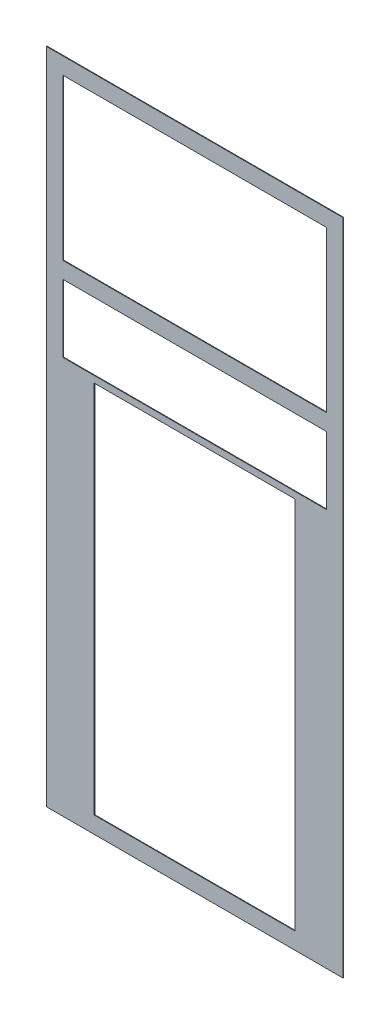
SolidWorks part; units mm, degrees
ref_plane "Alzado" through (0, 0, 0) normal (0, 0, 1) x (1, 0, 0)
ref_plane "Planta" through (0, 0, 0) normal (0, 1, 0) x (1, 0, 0)
ref_plane "Vista lateral" through (0, 0, 0) normal (1, 0, 0) x (0, 0, -1)
sketch "Croquis1" plane through (0, 0, 0) normal (0, 0, 1) x (1, 0, 0)
  line L0 (0, 0) -> (-900, 0)
  line L1 (-755, 1170.8) -> (-145, 1170.8)
  line L2 (-145, 1170.8) -> (-145, 50.8)
  line L3 (-145, 50.8) -> (-755, 50.8)
  line L4 (-755, 50.8) -> (-755, 1170.8)
  line L5 (-900, 0) -> (-900, 1190.8)
  line L6 (-900, 1190.8) -> (0, 1190.8)
  line L7 (0, 1190.8) -> (0, 0)
  dimension "D1" = 20
  dimension "D2" = 900
  dimension "D3" = 1190.8
  dimension "D4" = 1120
  dimension "D5" = 610
  dimension "D6" = 145
  dimension "D7" = 50.8
extrude "Saliente-Extruir1" add sketch "Croquis1" along normal blind 1.9
sketch "Croquis2" plane through (0, 0, 1.9) normal (0, 0, 1) x (1, 0, 0)
  line L0 (-900, 1190.8) -> (-900, 1460.8)
  line L1 (-900, 1460.8) -> (0, 1460.8)
  line L2 (0, 1460.8) -> (0, 1190.8)
  line L3 (0, 1190.8) -> (-900, 1190.8)
  dimension "D1" = 270
extrude "Saliente-Extruir2" add sketch "Croquis2" against normal blind 1.9
sketch "Croquis4" plane through (0, 0, 1.9) normal (0, 0, 1) x (1, 0, 0)
  line L0 (-450, 1170.8) -> (-450, 1460.8) construction
  line L1 (-145, 1170.8) -> (-755, 1170.8) construction
  line L2 (0, 1460.8) -> (-900, 1460.8) construction
  line L3 (-450, 1460.8) -> (-450, 1315.8) construction
  line L4 (-450, 1315.8) -> (0, 1315.8) construction
  line L5 (0, 0) -> (0, 1460.8) construction
  line L7 (-850, 1425.8) -> (-50, 1425.8)
  line L8 (-850, 1425.8) -> (-850, 1205.8)
  line L9 (-850, 1205.8) -> (-50, 1205.8)
  line L10 (-50, 1425.8) -> (-50, 1205.8)
  line L11 (-850, 1425.8) -> (-50, 1205.8) construction
  line L12 (-850, 1205.8) -> (-50, 1425.8) construction
  dimension "D1" = 800
  dimension "D2" = 220
extrude "Cortar-Extruir1" cut sketch "Croquis4" against normal blind 1.9
sketch "Croquis6" plane through (0, 0, 1.9) normal (0, 0, 1) x (1, 0, 0)
  line L0 (-755, 1170.8) -> (-755, 1185.8)
  line L1 (-755, 1185.8) -> (-145, 1185.8)
  line L2 (-145, 1185.8) -> (-145, 1170.8)
  line L3 (-145, 1170.8) -> (-755, 1170.8)
  dimension "D1" = 15
extrude "Cortar-Extruir2" cut sketch "Croquis6" against normal blind 10
sketch "Croquis7" plane through (0, 0, 1.9) normal (0, 0, 1) x (1, 0, 0)
  line L0 (-850, 1425.8) -> (-850, 1410.9)
  line L1 (-850, 1425.8) -> (-850, 1205.8) construction
  line L2 (-850, 1410.9) -> (-50, 1410.9)
  line L3 (-50, 1205.8) -> (-50, 1425.8) construction
  line L4 (-50, 1410.9) -> (-50, 1425.8)
  line L5 (-50, 1425.8) -> (-850, 1425.8)
  dimension "D1" = 14.9
extrude "Saliente-Extruir3" add sketch "Croquis7" against normal blind 1.9
sketch "Croquis8" plane through (0, 0, 0) normal (0, 0, -1) x (-1, 0, 0)
  line L0 (0, 1460.8) -> (50.8, 1460.8)
  line L1 (0, 1460.8) -> (900, 1460.8)
  line L2 (900, 1460.8) -> (900, 1998)
  line L3 (900, 1998) -> (0, 1998)
  line L4 (0, 1998) -> (0, 1460.8)
  line L5 (50.8, 1461.7) -> (50.8, 1449) construction
  line L6 (50.8, 1460.8) -> (50.8, 1947.2)
  line L7 (50.8, 1947.2) -> (849.2, 1947.2)
  line L8 (849.2, 1947.2) -> (849.2, 1460.8)
  line L9 (849.2, 1449) -> (849.2, 1461.7) construction
  line L10 (849.2, 1460.8) -> (900, 1460.8)
  line M12 (900, 1460.8) -> (0, 1460.8)
extrude "Saliente-Extruir4" add sketch "Croquis8" against normal blind 1.9 contours L7 L8 L2 L3 L4 L6 M12
